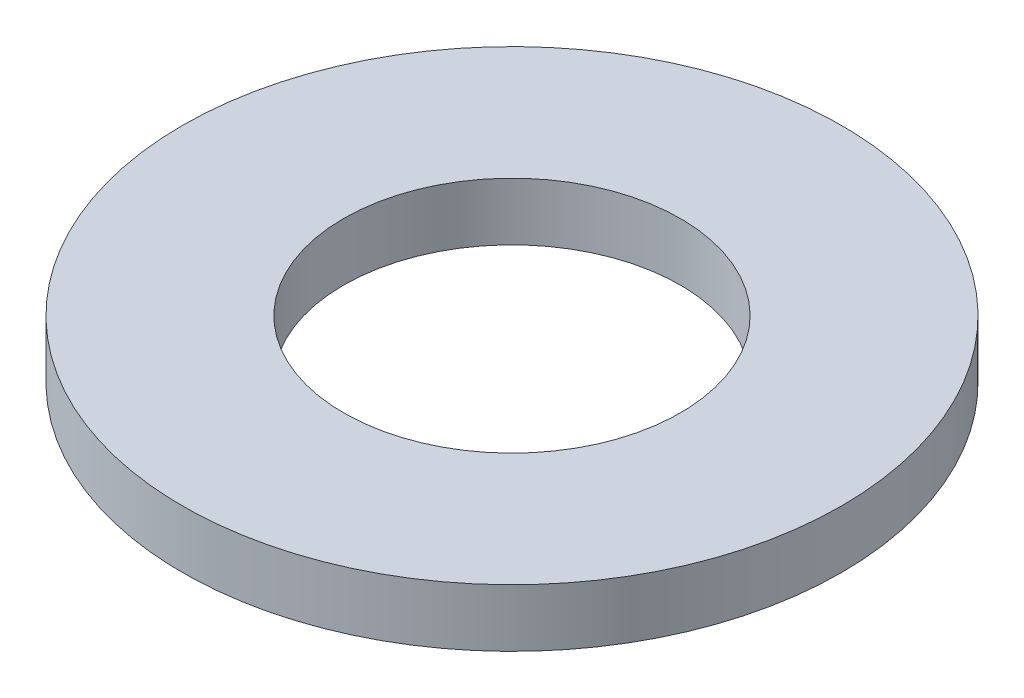
SolidWorks part; units mm, degrees
ref_plane "Plano frontal" through (0, 0, 0) normal (0, 0, 1) x (1, 0, 0)
ref_plane "Plano superior" through (0, 0, 0) normal (0, 1, 0) x (1, 0, 0)
ref_plane "Plano direito" through (0, 0, 0) normal (1, 0, 0) x (0, 0, -1)
sketch "Esboço1" plane through (0, 0, 0) normal (0, 0, 1) x (1, 0, 0)
  line L0 (0, 35.4173) -> (0, -64.5274) construction
sketch "Esboço2" plane through (0, 0, 0) normal (0, 0, 1) x (1, 0, 0)
  line L0 (1.75, 0.3) -> (1.75, -0.3)
  line L1 (1.75, -0.3) -> (3.425, -0.3)
  line L2 (3.425, -0.3) -> (3.425, 0.3)
  line L3 (3.425, 0.3) -> (1.75, 0.3)
  line L4 (0, 0) -> (1.75, 0) construction
  line L5 (0, 200035.4173) -> (0, -200064.5274) construction
  dimension "D1" = 0.6
  dimension "D2" = 3.425
  dimension "D3" = 1.75
revolve "Revolução1" add sketch "Esboço2" angle 360 about L0
